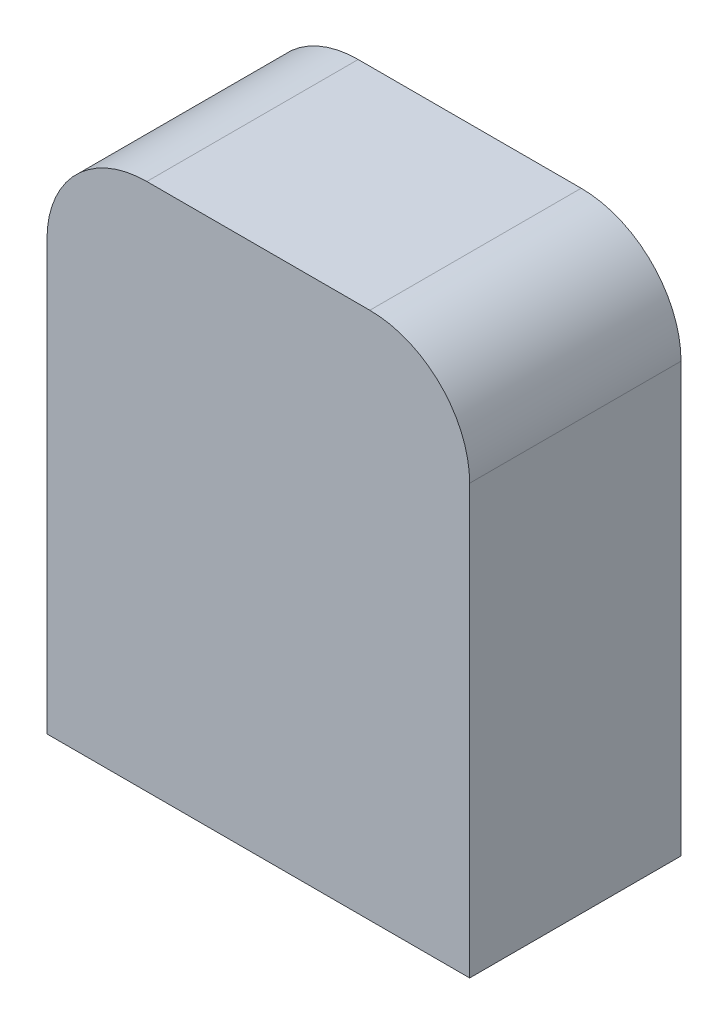
SolidWorks part; units mm, degrees
material "Balsa"
ref_plane "Front Plane" through (0, 0, 0) normal (0, 0, 1) x (1, 0, 0)
ref_plane "Top Plane" through (0, 0, 0) normal (0, 1, 0) x (1, 0, 0)
ref_plane "Right Plane" through (0, 0, 0) normal (1, 0, 0) x (0, 0, -1)
sketch "Sketch1" plane through (0, 0, 0) normal (0, 0, 1) x (1, 0, 0)
  line L1 (0, 0) -> (12.7, 0)
  line L2 (0, 0) -> (0, 15.875)
  line L3 (0, 15.875) -> (12.7, 15.875)
  line L4 (12.7, 0) -> (12.7, 15.875)
  dimension "D1" = 12.7
  dimension "D2" = 15.875
extrude "Boss-Extrude1" add sketch "Sketch1" along normal blind 6.35
fillet "Fillet1" radius 3 2 edges at (0, 15.875, 3.175) (12.7, 15.875, 3.175)
